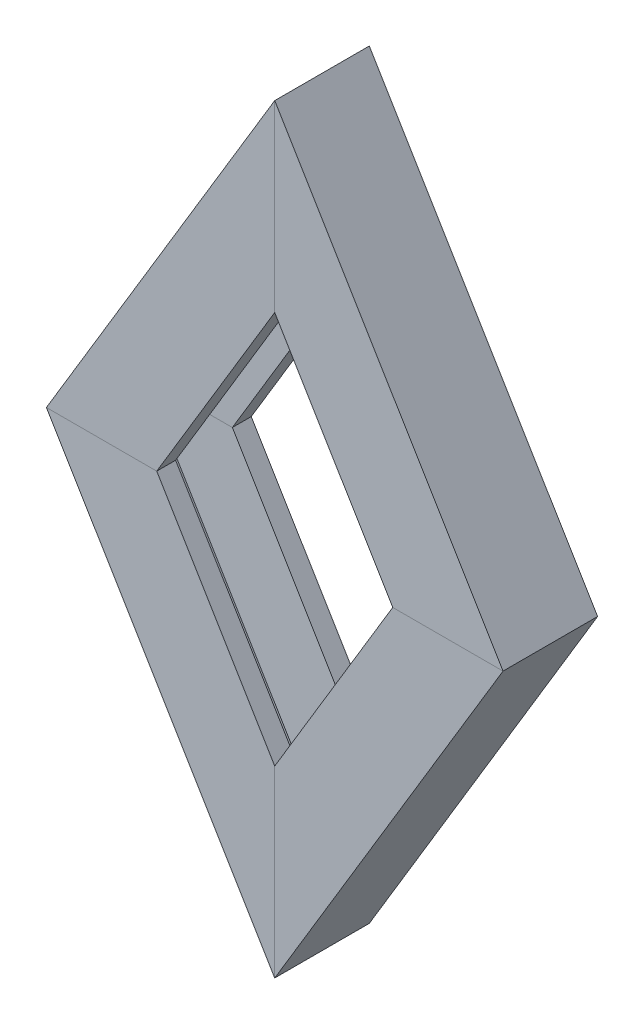
SolidWorks part; units mm, degrees
ref_plane "Front Plane" through (0, 0, 0) normal (0, 0, 1) x (1, 0, 0)
ref_plane "Top Plane" through (0, 0, 0) normal (0, 1, 0) x (1, 0, 0)
ref_plane "Right Plane" through (0, 0, 0) normal (1, 0, 0) x (0, 0, -1)
sketch "Sketch1" plane through (0, 0, 0) normal (0, 0, 1) x (1, 0, 0)
  line L0 (0, 0) -> (-91.581, 152.4)
  line L1 (-91.581, 152.4) -> (0, 304.8)
  line L2 (0, 304.8) -> (91.581, 152.4)
  line L3 (91.581, 152.4) -> (0, 0)
  point P3 (0, 0)
  dimension "D1" = 177.8
  dimension "D2" = 304.8
other "Building C CHANEL(1)"
ref_plane "Plane2" through (-91.581, 152.4, 0) normal (0.5151, 0.8571, 0) x (0, 0, 1)
sketch "Sketch2" plane through (-91.581, 152.4, 0) normal (0.5151, 0.8571, 0) x (0, 0, 1)
  line L0 (-25, 25) -> (-25, -25)
  line L13 (-25, -25) -> (25, -25)
  line L14 (25, -25) -> (25, 25)
  line L15 (25, 25) -> (15, 25)
  line L16 (15, 25) -> (15, -15)
  line L17 (15, -15) -> (-15, -15)
  line L18 (-15, -15) -> (-15, 25)
  line L19 (-15, 25) -> (-25, 25)
  line L20 (-15, -15) -> (-15, -25) construction
  line L21 (-25, 25) -> (25, -25) construction
  point P8 (0, 0)
  point P9 (0, 0)
  dimension "D1" = 50
  dimension "D2" = 10
  dimension "D3" = 50
